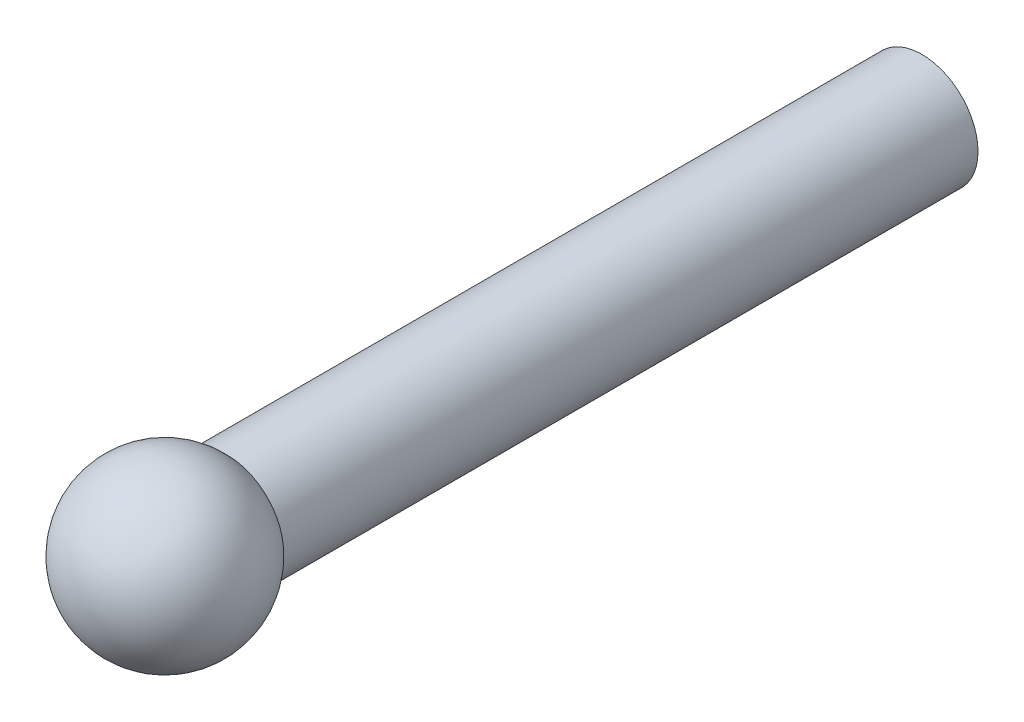
SolidWorks part; units mm, degrees
ref_plane "Piano frontale" through (0, 0, 0) normal (0, 0, 1) x (1, 0, 0)
ref_plane "Piano superiore" through (0, 0, 0) normal (0, 1, 0) x (1, 0, 0)
ref_plane "Piano destro" through (0, 0, 0) normal (1, 0, 0) x (0, 0, -1)
sketch "Schizzo1" plane through (0, 0, 0) normal (0, 0, 1) x (1, 0, 0)
  circle A0 centre (0, 0) radius 2
  dimension "D1" = 4
extrude "Estrusione-Estrusione1" add sketch "Schizzo1" along normal blind 25
sketch "Schizzo3" plane through (0, 0, 0) normal (0, 1, 0) x (1, 0, 0)
  line L0 (-2, -25) -> (2, -25) construction
  line L1 (-2, -25) -> (2, -25)
  line L2 (0, -25) -> (0, -27)
  line L3 (-3.329, -27) -> (3.9624, -27)
  circle A0 centre (0, -27) radius 3
  dimension "D2" = 6
  dimension "D1" = 2
revolve "Rivoluzione2" add sketch "Schizzo3" angle 360 about L3
